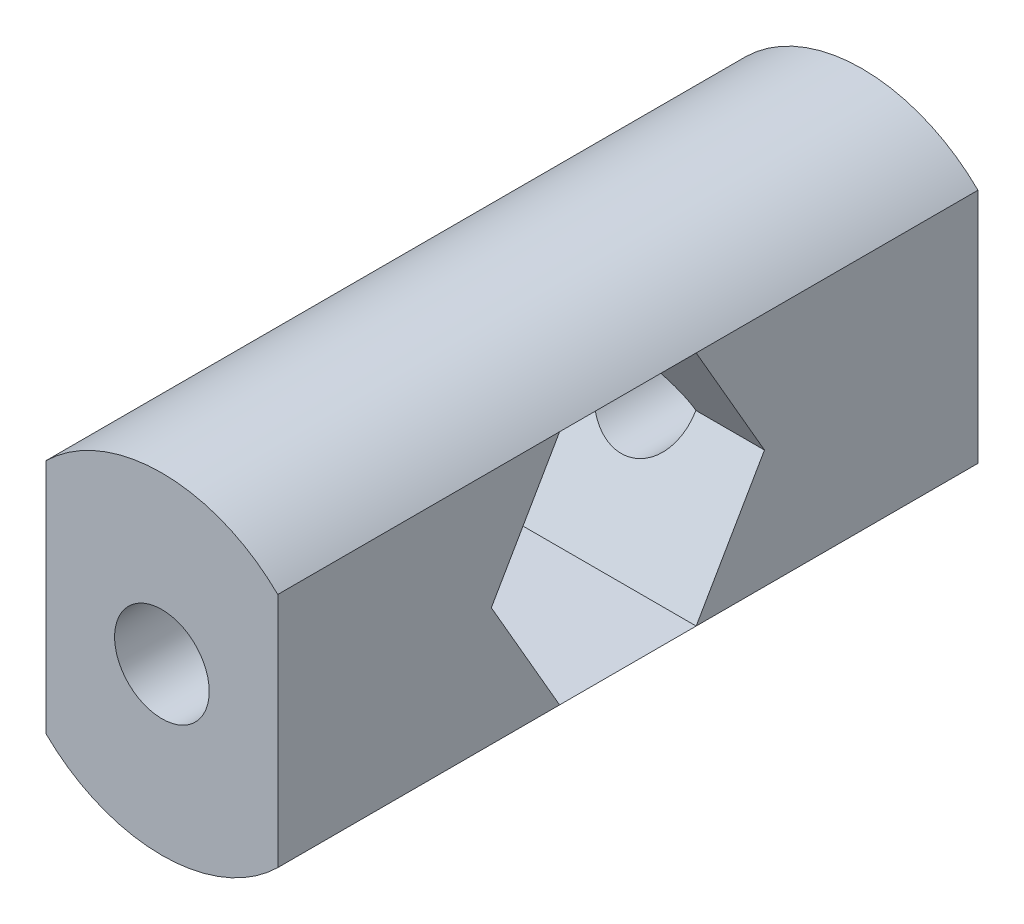
SolidWorks part; units mm, degrees
ref_plane "Front Plane" through (0, 0, 0) normal (0, 0, 1) x (1, 0, 0)
ref_plane "Top Plane" through (0, 0, 0) normal (0, 1, 0) x (1, 0, 0)
ref_plane "Right Plane" through (0, 0, 0) normal (1, 0, 0) x (0, 0, -1)
sketch "Sketch1" plane through (0, 0, 0) normal (0, 0, 1) x (1, 0, 0)
  circle A0 centre (0, 0) radius 17.5
  dimension "D1" = 35
extrude "Boss-Extrude1" add sketch "Sketch1" along normal mid plane 74
sketch "Sketch3" plane through (0, 0, 37) normal (0, 0, 1) x (1, 0, 0)
  line L0 (12.2474, 12.5) -> (12.2474, -12.5) construction
  line L1 (0, 17.5) -> (0, -18.2305) construction
  line L2 (-12.2474, -12.5) -> (-33.4239, -12.5)
  line L3 (12.2474, 12.5) -> (33.4239, 12.5)
  line L4 (12.2474, 12.5) -> (12.2474, -12.5)
  line L5 (12.2474, -12.5) -> (33.4239, -12.5)
  line L6 (33.4239, 12.5) -> (33.4239, -12.5)
  line L7 (-33.4239, 12.5) -> (-33.4239, -12.5)
  line L8 (-12.2474, 12.5) -> (-33.4239, 12.5)
  line L9 (-12.2474, 12.5) -> (-12.2474, -12.5)
  circle A0 centre (0, 0) radius 17.5 construction
  dimension "D1" = 25
extrude "Cut-Extrude1" cut sketch "Sketch3" against normal blind 74
sketch "Sketch4" plane through (0, 0, 37) normal (0, 0, 1) x (1, 0, 0)
  circle A0 centre (0, 0) radius 5
  dimension "D1" = 10
extrude "Cut-Extrude2" cut sketch "Sketch4" against normal blind 74
sketch "Sketch5" plane through (12.2474, 0, 0) normal (1, 0, 0) x (0, 0, -1)
  line L1 (14.4338, 0) -> (7.2169, 12.5)
  line L2 (7.2169, 12.5) -> (-7.2169, 12.5)
  line L3 (-7.2169, 12.5) -> (-14.4338, 0)
  line L4 (-14.4338, 0) -> (-7.2169, -12.5)
  line L5 (-7.2169, -12.5) -> (7.2169, -12.5)
  line L6 (7.2169, -12.5) -> (14.4338, 0)
  circle A0 centre (0, 0) radius 12.5 construction
  dimension "D1" = 25
extrude "Cut-Extrude3" cut sketch "Sketch5" against normal blind 74
